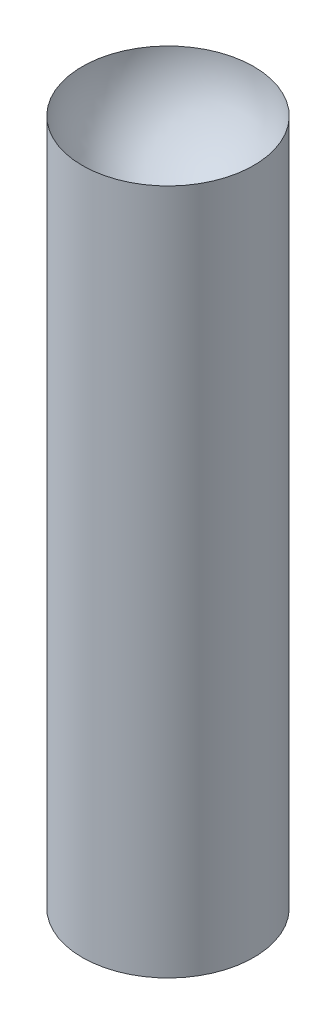
SolidWorks part; units mm, degrees
ref_plane "Front Plane" through (0, 0, 0) normal (0, 0, 1) x (1, 0, 0)
ref_plane "Top Plane" through (0, 0, 0) normal (0, 1, 0) x (1, 0, 0)
ref_plane "Right Plane" through (0, 0, 0) normal (1, 0, 0) x (0, 0, -1)
sketch "Sketch1" plane through (0, 0, 0) normal (0, 1, 0) x (1, 0, 0)
  circle A0 centre (0, 0) radius 12.7
extrude "Boss-Extrude1" add sketch "Sketch1" along normal blind 101.6
sketch "Sketch2" plane through (0, 101.6, 0) normal (0, 1, 0) x (1, 0, 0)
  line L0 (0, 12.7) -> (0, -12.7)
  line L1 (0, 12.7) -> (0, -12.7) construction
  arc A0 (0, 12.7) -> (0, -12.7) centre (0, 0) ccw
revolve "Cut-Revolve1" cut sketch "Sketch2" angle 360 about L1
sketch "Sketch4" plane through (0, 0, 0) normal (0, -1, 0) x (-1, 0, 0)
  line L0 (0, 11.43) -> (0, -11.43)
  line L1 (0, 11.43) -> (0, -11.43) construction
  arc A0 (0, -11.43) -> (0, 11.43) centre (0, 0) ccw
revolve "Cut-Revolve3" cut sketch "Sketch4" angle 360 about L1
